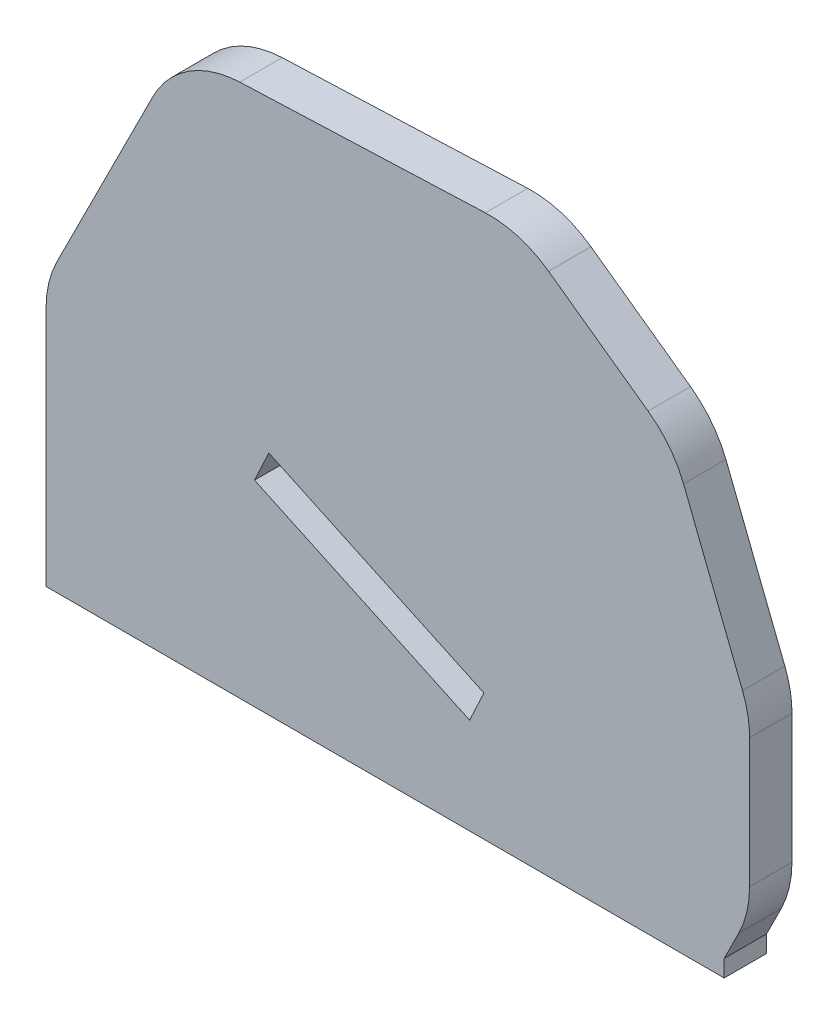
SolidWorks part; units mm, degrees
material "PBT General Purpose"
ref_plane "Front Plane" through (0, 0, 0) normal (0, 0, 1) x (1, 0, 0)
ref_plane "Top Plane" through (0, 0, 0) normal (0, 1, 0) x (1, 0, 0)
ref_plane "Right Plane" through (0, 0, 0) normal (1, 0, 0) x (0, 0, -1)
sketch "frame_outline" plane through (0, 0, 0) normal (0, 0, 1) x (1, 0, 0)
  line L0 (0, 0) -> (4, 0)
  line L1 (4, 0) -> (4, 0.1)
  line L2 (4, 0.1) -> (4.15, 0.4)
  line L3 (4.15, 0.4) -> (4.15, 1.4161)
  line L19 (4.15, 1.4161) -> (3.6952, 2.5687)
  line L20 (3.6952, 2.5687) -> (2.7971, 3.2123)
  line L21 (2.7971, 3.2123) -> (0.7894, 3.134)
  line L62 (0.7894, 3.134) -> (0, 1.5628)
  line L63 (0, 1.5628) -> (0, 0)
  line L64 (1.2298, 1.1578) -> (2.4986, 0.5662)
  line L65 (1.2298, 1.1578) -> (1.3143, 1.3391)
  line L66 (2.4986, 0.5662) -> (2.5831, 0.7474)
  line L67 (1.3143, 1.3391) -> (2.5831, 0.7474)
  line L68 (1.272, 1.2484) -> (2.5409, 0.6568) construction
  dimension "D1" = 4
  dimension "D6" = 0.1
  dimension "D7" = 0.15
  dimension "D8" = 0.3
  dimension "D12" = 0.2
  dimension "D13" = 1.4
  dimension "D14" = 25
  dimension "D3" = 1.6
extrude "Boss-Extrude1" add sketch "frame_outline" along normal mid plane 0.25
fillet "Fillet1" radius 0.6 6 edges at (4.15, 0.4, 0) (4.15, 1.4161, 0) (3.6952, 2.5687, 0) (2.7971, 3.2123, 0) (0.7894, 3.134, 0) (0, 1.5628, 0)
equation "\"t\"= 0.25'thickness of the sheets"
equation "\"t_cf\"= 0.115'thickness of single carbon fiber layer"
equation "\"t_kapton\"= 0.025'thickness of single Kapton flex layer"
equation "\"t_fr4\"= 0.1'thickness of FR4 with copper layer"
equation "\"joint_flex\"= 0.1'Width of flextures gap"
equation "\"joint_flex_eff\"= 0.02'Width of flecture after castelation"
equation "\"joint_fold\"= 0.2'Width of folding joints for 90deg fold"
equation "\"gap_tolerance\"= 0.002'Width to have interfecence fit between carbon fiber inserts"
equation "\"assemble_angle\"= 90'Angle of assembly parts"
equation "\"D1@Boss-Extrude1\"=\"t\""
equation "\"D12@frame_outline\"=\"t_fr4\"*2"
equation "\"link_lift\"= 0.5'Actuation linkage amplification for the lift motion"
equation "\"link_swing\"= 0.45'Actuation linkage amplification for the swing motion"
